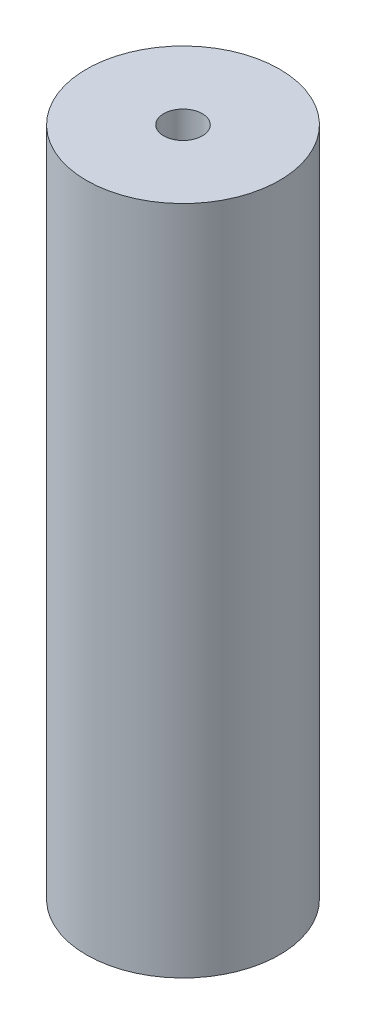
SolidWorks part; units mm, degrees
material "Nitrato de Sódio-Sacarose"
ref_plane "Plano frontal" through (0, 0, 0) normal (0, 0, 1) x (1, 0, 0)
ref_plane "Plano superior" through (0, 0, 0) normal (0, 1, 0) x (1, 0, 0)
ref_plane "Plano direito" through (0, 0, 0) normal (1, 0, 0) x (0, 0, -1)
sketch "Esboço1" plane through (0, 0, 0) normal (0, 1, 0) x (1, 0, 0)
  circle A0 centre (0, 0) radius 20
  circle A1 centre (0, 0) radius 4
  dimension "D1" = 40
  dimension "D2" = 8
extrude "Ressalto-extrusão1" add sketch "Esboço1" against normal blind 139
